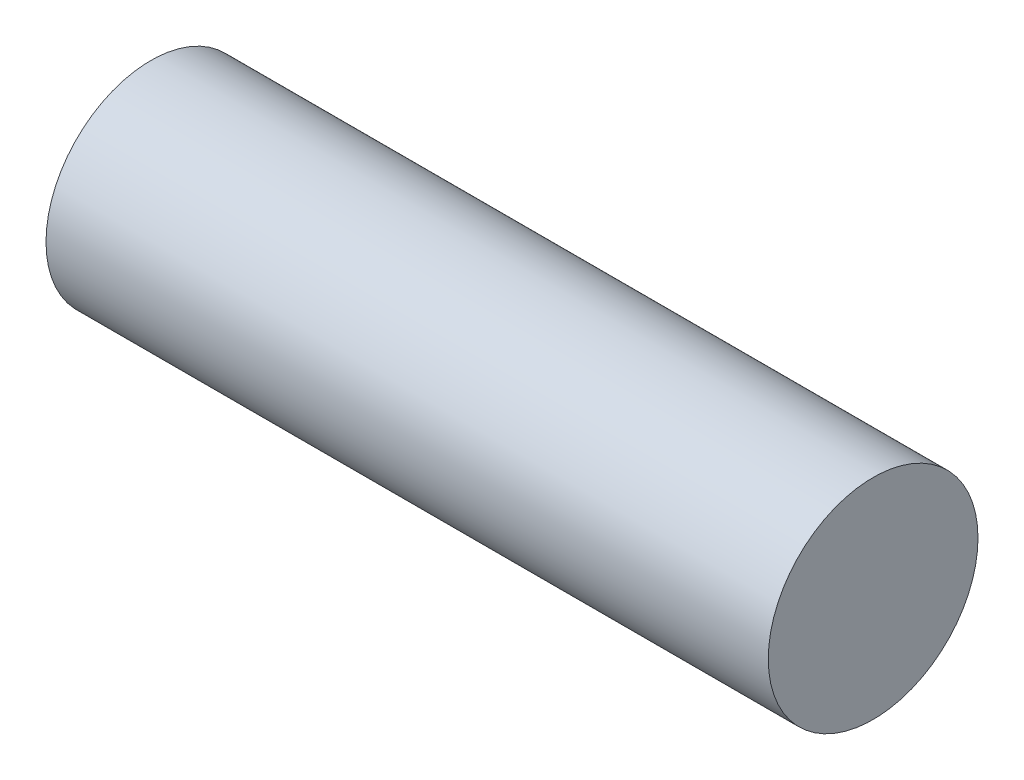
SolidWorks part; units mm, degrees
ref_plane "Front Plane" through (0, 0, 0) normal (0, 0, 1) x (1, 0, 0)
ref_plane "Top Plane" through (0, 0, 0) normal (0, 1, 0) x (1, 0, 0)
ref_plane "Right Plane" through (0, 0, 0) normal (1, 0, 0) x (0, 0, -1)
sketch "Sketch1" plane through (0, 0, 0) normal (1, 0, 0) x (0, 0, -1)
  circle A0 centre (0, 0) radius 4
  dimension "D1" = 8
extrude "Boss-Extrude1" add sketch "Sketch1" along normal blind 27.55
